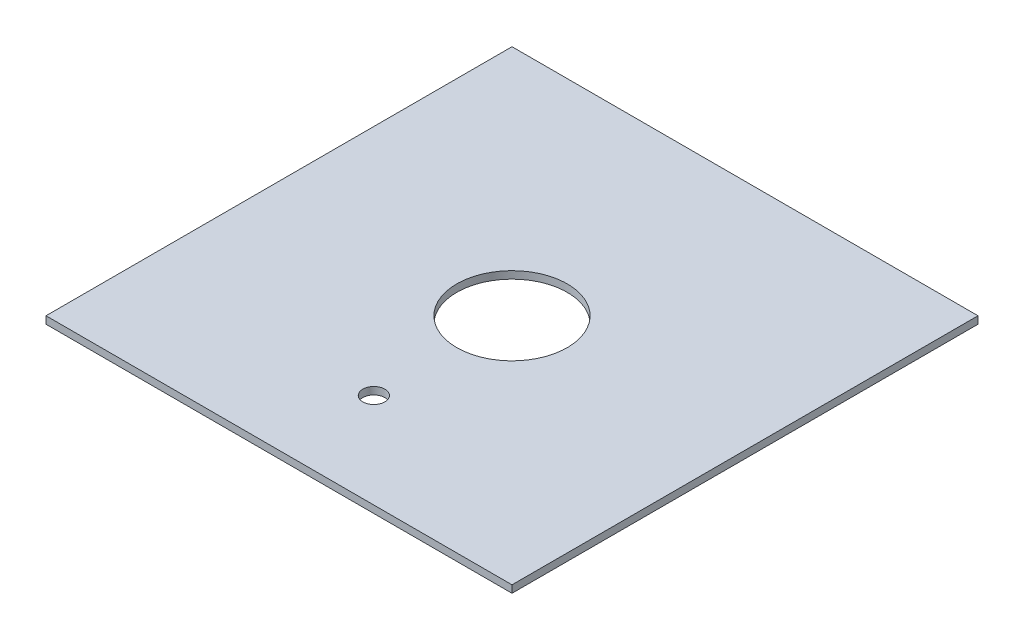
SolidWorks part; units mm, degrees
ref_plane "Front Plane" through (0, 0, 0) normal (0, 0, 1) x (1, 0, 0)
ref_plane "Top Plane" through (0, 0, 0) normal (0, 1, 0) x (1, 0, 0)
ref_plane "Right Plane" through (0, 0, 0) normal (1, 0, 0) x (0, 0, -1)
sketch "Sketch2" plane through (0, 0, 0) normal (0, 1, 0) x (1, 0, 0)
  line L1 (126.5, 126.5) -> (-126.5, 126.5)
  line L2 (126.5, 126.5) -> (126.5, -126.5)
  line L3 (126.5, -126.5) -> (-126.5, -126.5)
  line L4 (-126.5, 126.5) -> (-126.5, -126.5)
  line L5 (126.5, 126.5) -> (-126.5, -126.5) construction
  line L6 (126.5, -126.5) -> (-126.5, 126.5) construction
  point P0 (0, 0)
  dimension "D1" = 253
  dimension "D2" = 253
extrude "Boss-Extrude1" add sketch "Sketch2" along normal blind 4
sketch "Sketch3" plane through (0, 4, 0) normal (0, 1, 0) x (1, 0, 0)
  circle A0 centre (0, -75) radius 6
  circle A1 centre (0, 0) radius 30
  dimension "D1" = 12
  dimension "D2" = 60
  dimension "D3" = 75
extrude "Cut-Extrude1" cut sketch "Sketch3" against normal through all
